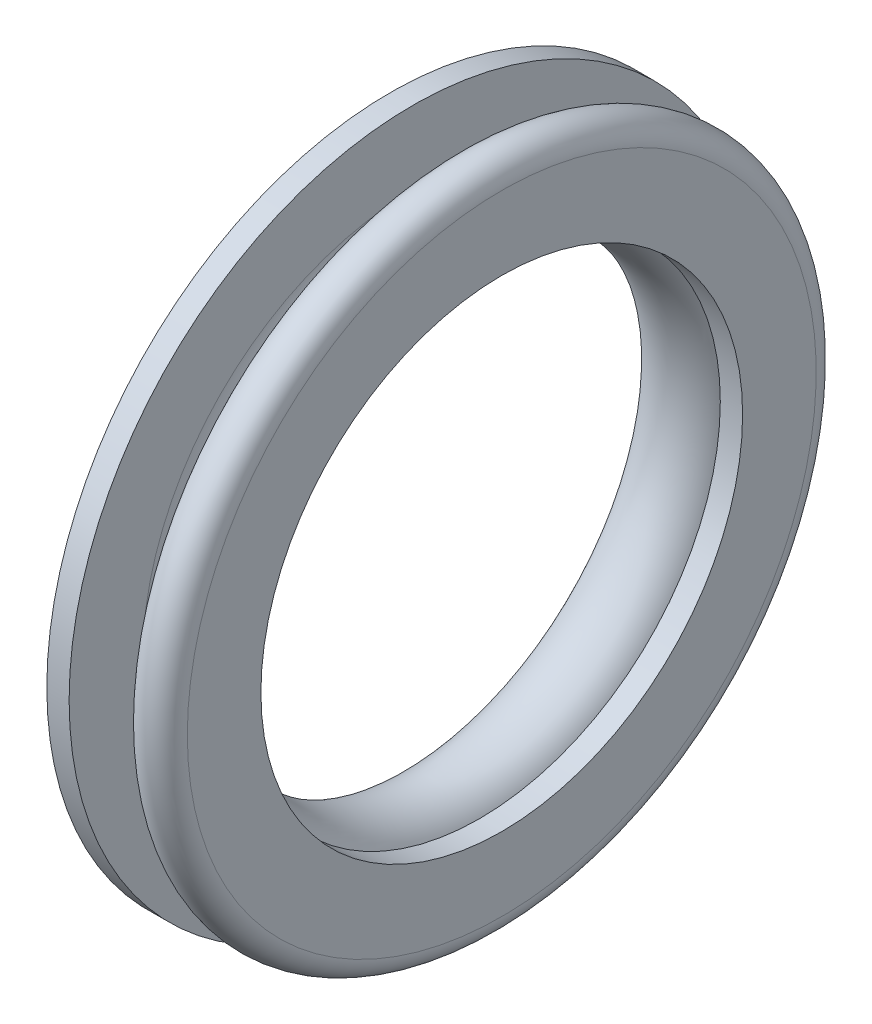
SolidWorks part; units mm, degrees
ref_plane "Front Plane" through (0, 0, 0) normal (0, 0, 1) x (1, 0, 0)
ref_plane "Top Plane" through (0, 0, 0) normal (0, 1, 0) x (1, 0, 0)
ref_plane "Right Plane" through (0, 0, 0) normal (1, 0, 0) x (0, 0, -1)
sketch "Sketch1" plane through (0, 0, 0) normal (0, 0, 1) x (1, 0, 0)
  line L0 (0, 0) -> (0, 7.7) construction
  line L1 (0, 0) -> (7.3291, 0) construction
  line L2 (0, 7.7) -> (0, 6.05)
  line L3 (2, 6.05) -> (2, 7.05) construction
  line L4 (2.5, 7.05) -> (2.5, 5.4)
  line L5 (0.5, 7.7) -> (0.5, 6.05)
  line L6 (1.5, 6.05) -> (1.5, 7.05)
  line L7 (2, 7.05) -> (2, 5.4) construction
  line L8 (0, 7.7) -> (0.5, 7.7)
  line L9 (2, 5.4) -> (2.5, 5.4)
  line L10 (1.5, 7.05) -> (2, 7.05) construction
  line L11 (2, 6.05) -> (2, 5.4)
  arc A0 (0, 6.05) -> (2, 6.05) centre (1, 6.05) ccw
  arc A1 (1.5, 7.05) -> (2.5, 7.05) centre (2, 7.05) cw
  arc A2 (0.5, 6.05) -> (1.5, 6.05) centre (1, 6.05) ccw
  dimension "D3" = 1
  dimension ".5" = 0.5
  dimension "D1" = 7.7
  dimension "D2" = 1.65
  dimension "D4" = 1
  dimension "D6" = 1.65
  dimension "D7" = 0.5
  dimension "D8" = 0.5
revolve "Revolve1" add sketch "Sketch1" angle 360 about L1
